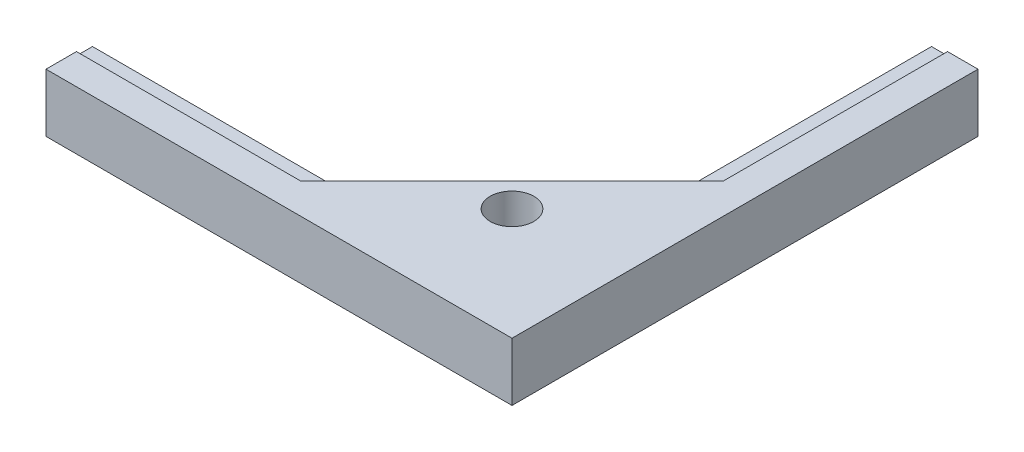
SolidWorks part; units mm, degrees
ref_plane "前视基准面" through (0, 0, 0) normal (0, 0, 1) x (1, 0, 0)
ref_plane "上视基准面" through (0, 0, 0) normal (0, 1, 0) x (1, 0, 0)
ref_plane "右视基准面" through (0, 0, 0) normal (1, 0, 0) x (0, 0, -1)
other "Configuration Table"
sketch "草图1" plane through (0, 0, 0) normal (0, 1, 0) x (1, 0, 0)
  line L0 (0, 0) -> (0, 64)
  line L1 (0, 64) -> (-4.1851, 64)
  line L2 (-4.1851, 64) -> (-4.1851, 33.1851)
  line L3 (-33.1851, 4.1851) -> (-64, 4.1851)
  line L4 (-64, 4.1851) -> (-64, 0)
  line L5 (-64, 0) -> (0, 0)
  line L6 (-4.1851, 33.1851) -> (-33.1851, 4.1851)
  line L7 (-18.6851, 18.6851) -> (0, 0) construction
  circle A0 centre (-15.3851, 15.3851) radius 3
  point P11 (0, 0)
  dimension "D5" = 29
  dimension "D6" = 6
  dimension "D4" = 15.3851
  dimension "D1" = 64
  dimension "D2" = 135
  dimension "D3" = 45
  dimension "D7" = 4.1851
extrude "凸台-拉伸1" add sketch "草图1" along normal blind 8
sketch "草图2" plane through (-4.1851, 0, 0) normal (-1, 0, 0) x (0, 0, 1)
  line L0 (-64, 8) -> (-64, 0) construction
  line L1 (-64, 7.6) -> (-33.1851, 7.6)
  line L2 (-64, 7.6) -> (-64, 0.4)
  line L3 (-64, 0.4) -> (-33.1851, 0.4)
  line L4 (-33.1851, 7.6) -> (-33.1851, 0.4)
  line L5 (-33.1851, 8) -> (-33.1851, 0) construction
  line L6 (-64, 0) -> (-33.1851, 0) construction
  line L7 (-64, 8) -> (-33.1851, 8) construction
  point P6 (0, 0)
  point P7 (-33.1851, 7.0931)
  dimension "D1" = 0.4
  dimension "D2" = 0.4
extrude "凸台-拉伸2" [suppressed] add sketch "草图2" along normal blind 2.2
sketch "草图4" plane through (0, 0, 0) normal (0, -1, 0) x (1, 0, 0)
  line L0 (-6.3851, -30.9851) -> (-6.3851, -64)
  line L1 (-4.1851, -33.1851) -> (-33.1851, -4.1851) construction
  line L2 (-6.3851, -64) -> (-4.1851, -64)
  line L3 (-4.1851, -64) -> (-4.1851, -33.1851)
  line L4 (-4.1851, -33.1851) -> (-6.3851, -30.9851)
  line L5 (0, -64) -> (-4.1851, -64) construction
  line L6 (-64, -4.1851) -> (-64, -6.3851)
  line L7 (-64, -6.3851) -> (-30.9851, -6.3851)
  line L8 (-30.9851, -6.3851) -> (-33.1851, -4.1851)
  line L9 (-33.1851, -4.1851) -> (-64, -4.1851)
  dimension "D1" = 2.2
extrude "凸台-拉伸3" add sketch "草图4" along normal mid plane 7 from offset 4
